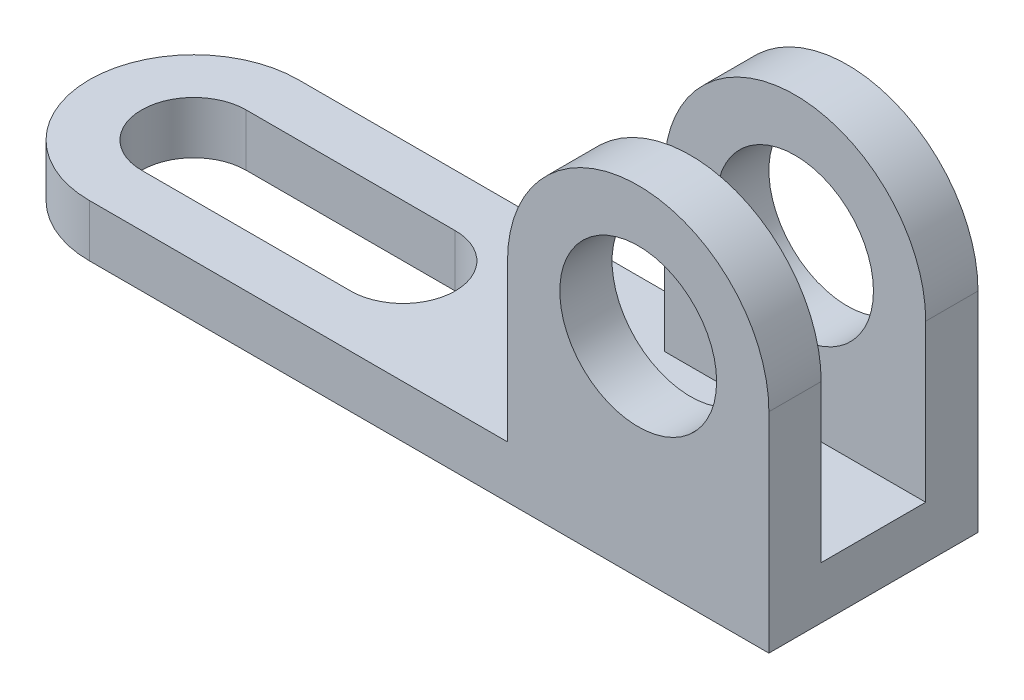
SolidWorks part; units mm, degrees
ref_plane "Front Plane" through (0, 0, 0) normal (0, 0, 1) x (1, 0, 0)
ref_plane "Top Plane" through (0, 0, 0) normal (0, 1, 0) x (1, 0, 0)
ref_plane "Right Plane" through (0, 0, 0) normal (1, 0, 0) x (0, 0, -1)
sketch "Sketch5" plane through (0, 0, 0) normal (0, 1, 0) x (1, 0, 0)
  line L0 (0, 20) -> (0, -20)
  line L1 (0, -20) -> (-130, -20)
  line L3 (-130, 20) -> (0, 20)
  arc A0 (-130, 20) -> (-130, -20) centre (-130, 0) ccw
  dimension "D1" = 130
  dimension "D2" = 40
extrude "Boss-Extrude4" add sketch "Sketch5" along normal blind 10
sketch "Sketch6" plane through (0, 10, 0) normal (0, 1, 0) x (1, 0, 0)
  line L0 (0, -20) -> (0, 20) construction
  line L1 (-50, 20) -> (0, 20)
  line L2 (-50, 20) -> (-50, -20)
  line L4 (-50, -20) -> (0, -20)
  line L5 (0, 20) -> (0, -20)
  line L6 (-25, -20) -> (-25, 20) construction
  line L7 (-50, 0) -> (0, 0) construction
  line L8 (0, 20) -> (-130, 20) construction
  line L9 (-130, -20) -> (0, -20) construction
  point P0 (-25, 0)
  dimension "D1" = 50
extrude "Boss-Extrude7" add sketch "Sketch6" along normal blind 70
sketch "Sketch9" plane through (0, 0, 20) normal (0, 0, 1) x (1, 0, 0)
  line L1 (0, 80) -> (0, 0) construction
  line L4 (-50, 80) -> (-50, 10) construction
  line L5 (-50, 40) -> (-50, 80)
  line L6 (-50, 80) -> (0, 80)
  line L7 (0, 80) -> (0, 40)
  arc A0 (-50, 40) -> (0, 40) centre (-25, 40) cw
  dimension "D1" = 25
extrude "Cut-Extrude2" cut sketch "Sketch9" against normal through all
sketch "Sketch10" plane through (0, 0, 20) normal (0, 0, 1) x (1, 0, 0)
  line L0 (-50, 40) -> (-50, 10) construction
  circle A0 centre (-25, 40) radius 15
  point P2 (-24.6182, 43.7046)
  point P3 (0, 0)
  dimension "D1" = 30
  dimension "D2" = 25
extrude "Cut-Extrude3" cut sketch "Sketch10" against normal through all
sketch "Sketch11" plane through (0, 0, 0) normal (1, 0, 0) x (0, 0, -1)
  line L2 (-10, 80) -> (10, 80)
  line L3 (-10, 80) -> (-10, 10)
  line L4 (-10, 10) -> (10, 10)
  line L5 (10, 80) -> (10, 10)
  line L6 (0, 10) -> (0, 80) construction
  line L7 (-10, 45) -> (10, 45) construction
  line L8 (-20, 40) -> (-20, 0) construction
  line L9 (-20, 0) -> (20, 0) construction
  point P0 (0, 6.1934)
  point P3 (0, 45)
  dimension "D1" = 20
  dimension "D2" = 70
  dimension "D3" = 10
  dimension "D4" = 10
extrude "Cut-Extrude4" cut sketch "Sketch11" against normal through all
sketch "Sketch12" plane through (0, 10, 0) normal (0, 1, 0) x (1, 0, 0)
  line L0 (-130, 0) -> (-90, 0) construction
  line L1 (-130, 10) -> (-90, 10)
  line L2 (-130, -10) -> (-90, -10)
  arc A0 (-130, 10) -> (-130, -10) centre (-130, 0) ccw
  arc A1 (-90, -10) -> (-90, 10) centre (-90, 0) ccw
  point P3 (-110, 0)
  point P8 (0, 0)
  point P10 (-30.9545, 7.65)
  dimension "D1" = 10
  dimension "D2" = 40
  dimension "D3" = 130
extrude "Cut-Extrude5" cut sketch "Sketch12" against normal through all
